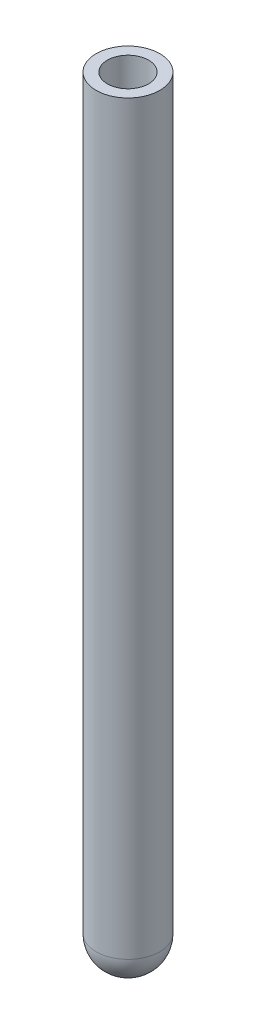
SolidWorks part; units mm, degrees
material "Nickel silver 65-12, UNS C75700"
ref_plane "Front" through (0, 0, 0) normal (0, 0, 1) x (1, 0, 0)
ref_plane "Top" through (0, 0, 0) normal (0, 1, 0) x (1, 0, 0)
ref_plane "Right" through (0, 0, 0) normal (1, 0, 0) x (0, 0, -1)
sketch "Sketch1" plane through (0, 0, 0) normal (1, 0, 0) x (0, 0, -1)
  line L0 (0.33, 0) -> (0.33, -10)
  line L1 (0.33, -10) -> (0, -10)
  line L2 (0, -10) -> (0, -12.45)
  line L3 (0, -12.45) -> (0.51, -12.45)
  line L8 (0.51, -12.45) -> (0.51, 0)
  line L11 (0.51, 0) -> (0.33, 0)
  dimension "D4" = 0.33
  dimension "D9" = 10
  dimension "D2" = 12.45
  dimension "D1" = 0.51
revolve "Revolve1" add sketch "Sketch1" angle 360 about L2
fillet "Fillet1" radius 0.5 1 edges at (0, -12.45, 0.51)
equation "\"D4@Sketch1\"=0.66/2"
equation "\"D1@Sketch1\"=1.02/2"
equation "\"D2@Sketch1\"=17.02-4.57"
